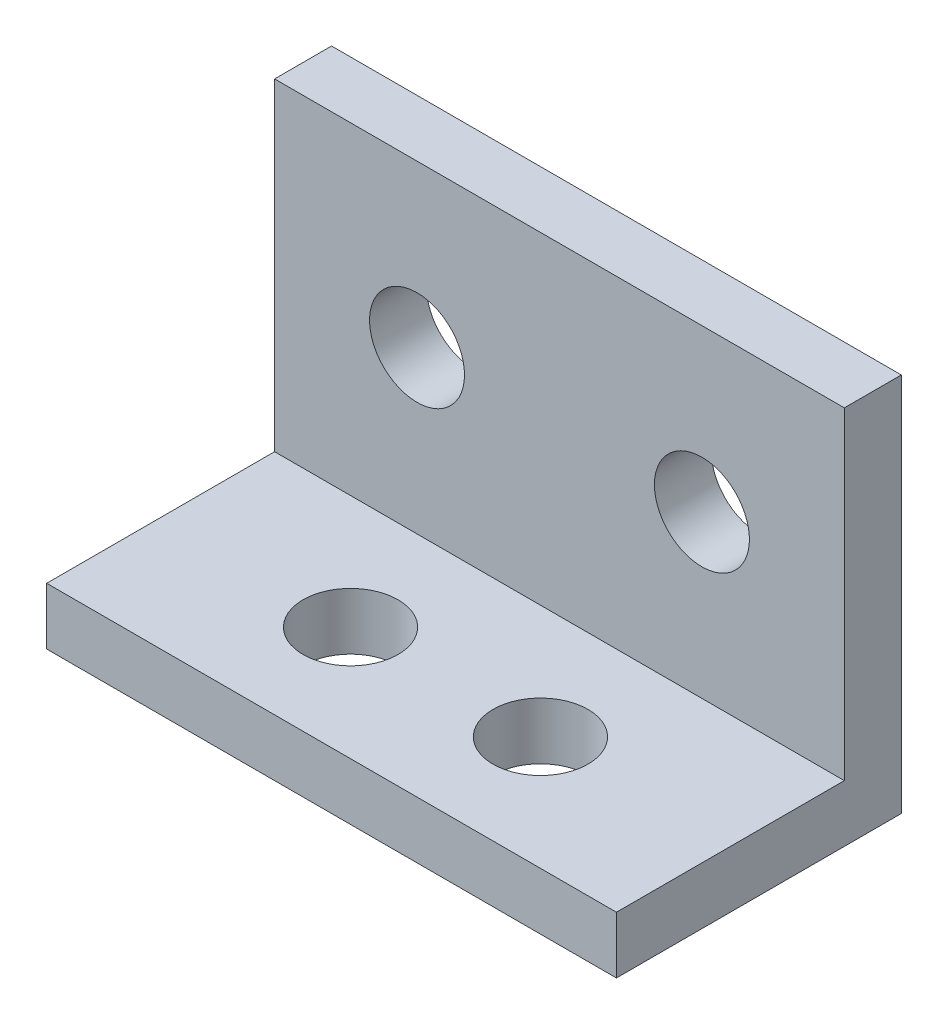
SolidWorks part; units mm, degrees
ref_plane "Front Plane" through (0, 0, 0) normal (0, 0, 1) x (1, 0, 0)
ref_plane "Top Plane" through (0, 0, 0) normal (0, 1, 0) x (1, 0, 0)
ref_plane "Right Plane" through (0, 0, 0) normal (1, 0, 0) x (0, 0, -1)
sketch "Sketch2" plane through (0, 0, 0) normal (1, 0, 0) x (0, 0, -1)
  line L1 (0, 0) -> (-19.05, 0)
  line L2 (0, 0) -> (0, 25.4)
  line L3 (0, 25.4) -> (-3.81, 25.4)
  line L4 (-19.05, 0) -> (-19.05, 3.81)
  line L7 (-19.05, 3.81) -> (-3.81, 3.81)
  line L8 (-3.81, 25.4) -> (-3.81, 3.81)
  dimension "D1" = 25.4
  dimension "D2" = 19.05
  dimension "D3" = 3.81
  dimension "D4" = 3.81
extrude "Boss-Extrude1" add sketch "Sketch2" along normal blind 38.1
sketch "Sketch3" plane through (0, 0, 3.81) normal (0, 0, 1) x (1, 0, 0)
  line L0 (19.05, 25.4) -> (19.05, 3.81) construction
  line L1 (38.1, 25.4) -> (0, 25.4) construction
  line L2 (38.1, 3.81) -> (0, 3.81) construction
  line L3 (19.05, 14.605) -> (0, 14.605) construction
  line L4 (0, 25.4) -> (0, 3.81) construction
  line L5 (0, 14.605) -> (38.1, 14.605) construction
  line L6 (38.1, 25.4) -> (38.1, 3.81) construction
  line L7 (9.525, 14.605) -> (9.525, 25.4) construction
  line L8 (9.525, 25.4) -> (9.525, 3.81) construction
  line L9 (38.1, 14.605) -> (19.05, 14.605) construction
  line L10 (19.05, 14.605) -> (38.1, 14.605) construction
  line L11 (38.1, 14.605) -> (28.575, 14.605) construction
  line L12 (28.575, 14.605) -> (28.575, 3.81) construction
  line L13 (28.575, 3.81) -> (28.575, 25.4) construction
  circle A0 centre (9.525, 14.605) radius 3.175
  circle A1 centre (28.575, 14.605) radius 3.175
  point P20 (0, 0)
  dimension "D1" = 6.35
extrude "Cut-Extrude1" cut sketch "Sketch3" against normal through all
sketch "Sketch4" plane through (0, 0, 0) normal (0, -1, 0) x (-1, 0, 0)
  line L3 (-19.05, -9.525) -> (-19.05, -19.05) construction
  line L4 (-38.1, -19.05) -> (0, -19.05) construction
  line L5 (-19.05, -19.05) -> (-19.05, 0) construction
  line L6 (-38.1, 0) -> (0, 0) construction
  circle A0 centre (-12.7, -11.43) radius 3.175
  circle A1 centre (-25.4, -11.43) radius 3.175
  point P0 (0, 0)
  dimension "D5" = 6.35
  dimension "D6" = 6.35
  dimension "D1" = 6.35
  dimension "D2" = 6.35
  dimension "D3" = 7.62
  dimension "D4" = 7.62
extrude "Cut-Extrude2" cut sketch "Sketch4" against normal blind 25.4
